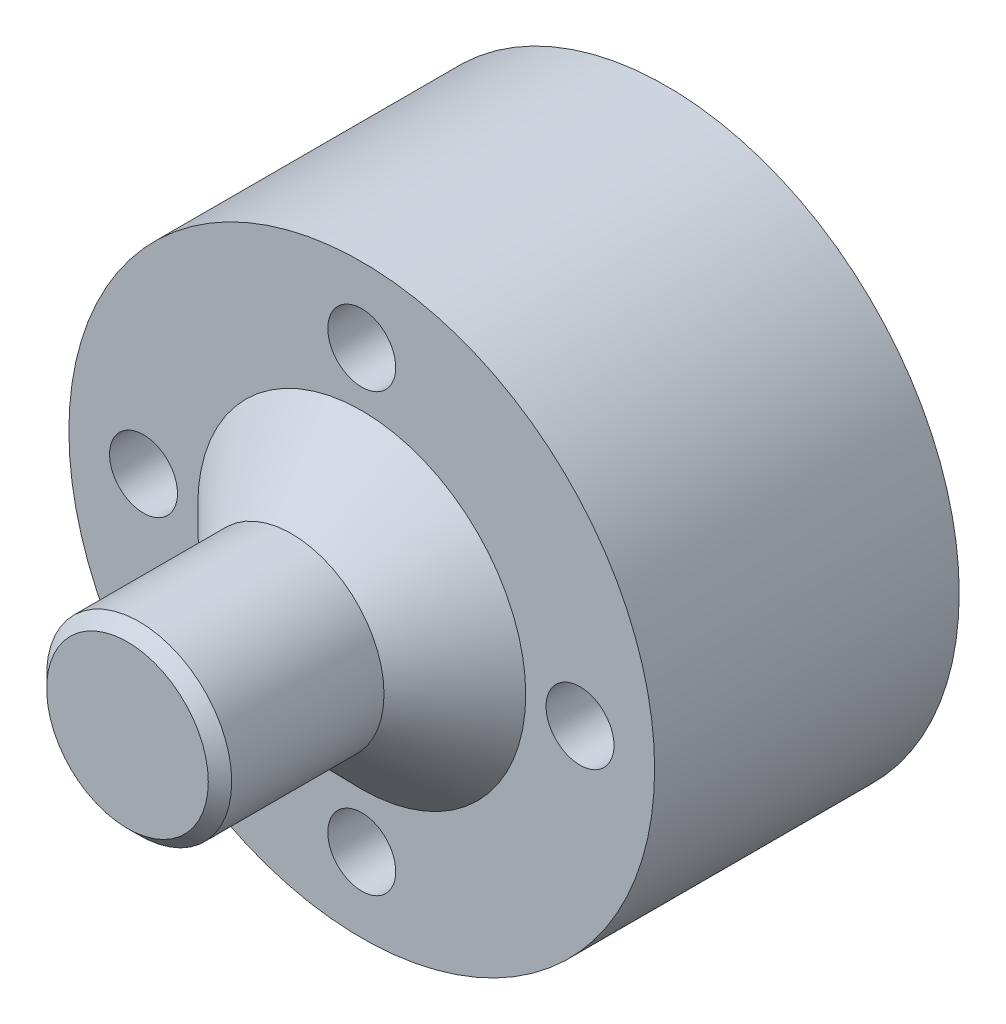
SolidWorks part; units mm, degrees
ref_plane "Front Plane" through (0, 0, 0) normal (0, 0, 1) x (1, 0, 0)
ref_plane "Top Plane" through (0, 0, 0) normal (0, 1, 0) x (1, 0, 0)
ref_plane "Right Plane" through (0, 0, 0) normal (1, 0, 0) x (0, 0, -1)
sketch "Sketch1" plane through (0, 0, 0) normal (0, 0, 1) x (1, 0, 0)
  circle A0 centre (0, 0) radius 12.5
  dimension "D2" = 25
extrude "Boss-Extrude1" add sketch "Sketch1" along normal mid plane 8
sketch "Sketch10" plane through (0, 0, 4) normal (0, 0, 1) x (1, 0, 0)
  circle A0 centre (0, 0) radius 12.5
  dimension "D1" = 25
sketch "Sketch8" plane through (0, 0, 4) normal (0, 0, 1) x (1, 0, 0)
  line L2 (-6.125, 6.125) -> (6.125, 6.125)
  line L3 (-6.125, 6.125) -> (-6.125, -6.125)
  line L4 (-6.125, -6.125) -> (6.125, -6.125)
  line L5 (6.125, 6.125) -> (6.125, -6.125)
  line L6 (-6.125, 6.125) -> (6.125, -6.125) construction
  line L7 (-6.125, -6.125) -> (6.125, 6.125) construction
  point P5 (0, 0)
  point P14 (0, 0)
  dimension "D1" = 12.25
extrude "Cut-Extrude1" cut sketch "Sketch8" against normal up to next
sketch "Sketch11" plane through (0, 0, 4) normal (0, 0, 1) x (1, 0, 0)
  line L0 (6.125, -6.125) -> (6.125, 6.125) construction
  circle A0 centre (9.315, 0) radius 1.45
  circle A1 centre (0, -9.315) radius 1.45
  circle A2 centre (-9.315, 0) radius 1.45
  circle A3 centre (0, 9.315) radius 1.45
  point P13 (0, 0)
  dimension "D1" = 2.9
  dimension "D2" = 3.19
  dimension "D3" = 4
extrude "Cut-Extrude4" cut sketch "Sketch11" against normal through all
sketch "Sketch14" plane through (0, 0, 4) normal (0, 0, 1) x (1, 0, 0)
  circle A0 centre (0, 0) radius 12.5
  circle A1 centre (0, 0) radius 12.5 construction
extrude "Boss-Extrude2" add sketch "Sketch14" along normal blind 5
sketch "Sketch13" plane through (0, 0, 0) normal (0, 1, 0) x (1, 0, 0)
  line L0 (0, -11.9651) -> (0, -27.8724) construction
  line L1 (0, -12) -> (3.95, -12)
  line L2 (-12.5, -9) -> (12.5, -9) construction
  line L3 (3.95, -12) -> (7.5, -8.5067)
  line L4 (7.5, -8.5067) -> (0, -8.5067)
  line L5 (0, -8.5067) -> (0, -12)
  dimension "D1" = 3.95
  dimension "D2" = 3
  dimension "D3" = 7.5
revolve "Revolve1" add sketch "Sketch13" angle 360 about L0
sketch "Sketch15" plane through (0, 0, 12) normal (0, 0, 1) x (1, 0, 0)
  circle A0 centre (0, 0) radius 3.95
extrude "Boss-Extrude3" add sketch "Sketch15" along normal blind 7
chamfer "Chamfer1" distance 0.5 angle 45 1 edges at (3.95, 0, 19)
sketch "Sketch18" plane through (0, 0, 9) normal (0, 0, 1) x (1, 0, 0)
  circle A0 centre (-9.315, 0) radius 1.45
  circle A1 centre (0, -9.315) radius 1.45
  circle A2 centre (9.315, 0) radius 1.45
  circle A3 centre (0, 9.315) radius 1.45
extrude "Cut-Extrude6" cut sketch "Sketch18" against normal blind 30
equation "\"drumDiameter\"= 25"
equation "\"D2@Sketch1\"= \"drumDiameter\""
equation "\"drumLength\"=8"
equation "\"foamThickness\"= 5"
equation "\"drumAbove\"= 0.6"
equation "\"holderThicc\"= 2"
equation "\"D1@Boss-Extrude1\"=\"drumLength\""
equation "\"squareBarLength\"= 12.25"
equation "\"D1@Sketch8\"=\"squareBarLength\""
equation "\"D1@Sketch10\"=\"drumDiameter\""
equation "\"toothlen\"= 2.5"
